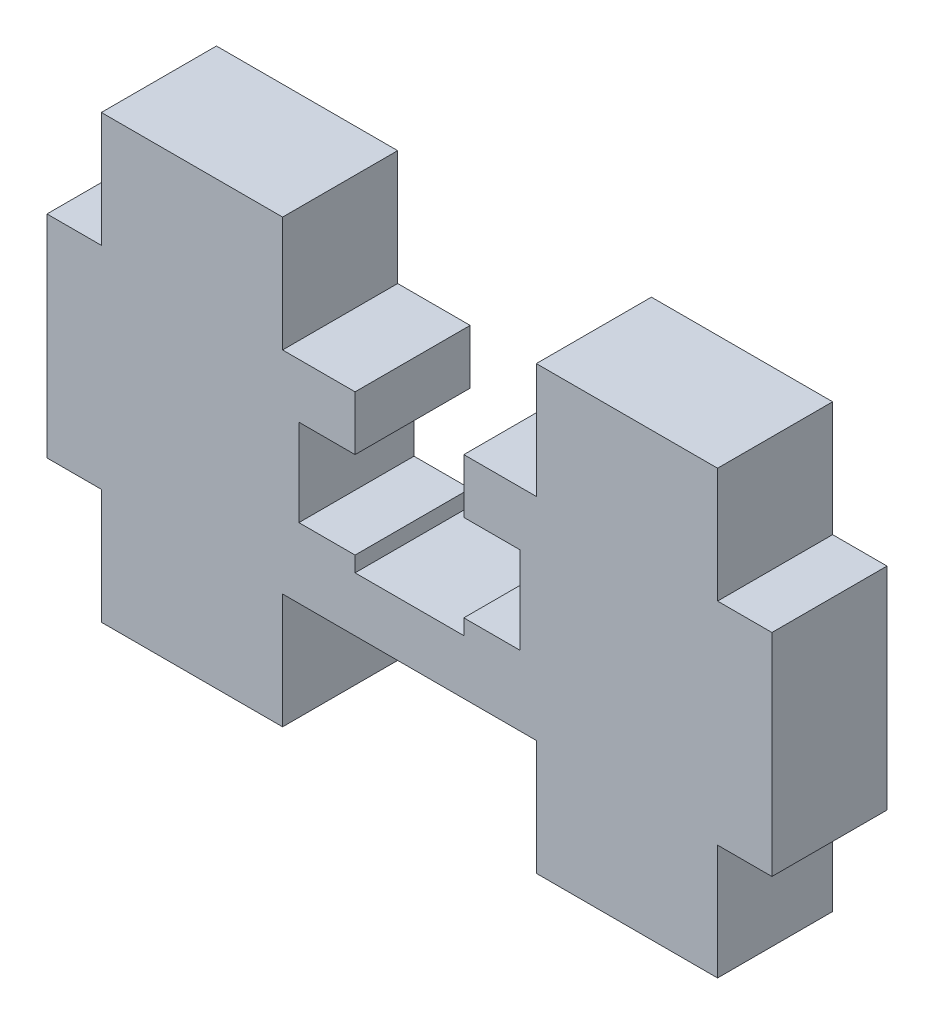
SolidWorks part; units mm, degrees
ref_plane "前视基准面" through (0, 0, 0) normal (0, 0, 1) x (1, 0, 0)
ref_plane "上视基准面" through (0, 0, 0) normal (0, 1, 0) x (1, 0, 0)
ref_plane "右视基准面" through (0, 0, 0) normal (1, 0, 0) x (0, 0, -1)
sketch "Sketch1" plane through (0, 0, 0) normal (0, 0, 1) x (1, 0, 0)
  line L0 (-5.1789, 0) -> (5.1005, 0) construction
  line L1 (0, 5.0769) -> (0, -5.0178) construction
  line L2 (-10, 2.915) -> (-10, -2.915)
  line L3 (-10, -2.915) -> (-8.5, -2.915)
  line L4 (-8.5, -2.915) -> (-8.5, -6.09)
  line L5 (-8.5, -6.09) -> (-3.5, -6.09)
  line L6 (-3.5, -6.09) -> (-3.5, -2.915)
  line L7 (-3.5, -2.915) -> (3.5, -2.915)
  line L8 (3.5, -6.09) -> (3.5, -2.915)
  line L9 (8.5, -6.09) -> (3.5, -6.09)
  line L10 (8.5, -2.915) -> (8.5, -6.09)
  line L11 (10, -2.915) -> (8.5, -2.915)
  line L12 (10, 2.915) -> (10, -2.915)
  line L13 (10, 2.915) -> (8.5, 2.915)
  line L14 (8.5, 2.915) -> (8.5, 6.09)
  line L15 (8.5, 6.09) -> (3.5, 6.09)
  line L16 (3.5, 6.09) -> (3.5, 2.915)
  line L17 (-3.5, 2.915) -> (3.5, 2.915)
  line L18 (-3.5, 6.09) -> (-3.5, 2.915)
  line L19 (-8.5, 6.09) -> (-3.5, 6.09)
  line L20 (-8.5, 2.915) -> (-8.5, 6.09)
  line L21 (-10, 2.915) -> (-8.5, 2.915)
  line L22 (-6, -6.09) -> (-6, -6.7618) construction
  line L23 (6, -6.09) -> (6, -7.2752) construction
  point P5 (0, 2.915)
  point P13 (0, -2.915)
  point P19 (10, 0)
  point P28 (-10, 0)
  point P33 (-9.25, 2.915)
  dimension "D1" = 5.83
  dimension "D2" = 5
  dimension "D3" = 20
  dimension "D4" = 12
  dimension "D5" = 3.175
extrude "Boss-Extrude1" add sketch "Sketch1" along normal blind 3.175
sketch "Sketch2" plane through (0, 0, 3.175) normal (0, 0, 1) x (1, 0, 0)
  line L0 (0, 2.915) -> (0, -4.2947) construction
  line L1 (3.5, 2.915) -> (-3.5, 2.915) construction
  line L2 (-1.5, 2.915) -> (-1.5, 1.415)
  line L3 (-1.5, 1.415) -> (-3.05, 1.415)
  line L4 (-3.05, 1.415) -> (-3.05, -0.985)
  line L5 (-3.05, -0.985) -> (-1.5, -0.985)
  line L6 (-1.5, -0.985) -> (-1.5, -1.41)
  line L7 (-1.5, -1.41) -> (1.5, -1.41)
  line L8 (-1.5, 2.915) -> (1.5, 2.915)
  line L9 (1.5, -0.985) -> (1.5, -1.41)
  line L10 (3.05, -0.985) -> (1.5, -0.985)
  line L11 (3.05, 1.415) -> (3.05, -0.985)
  line L12 (1.5, 1.415) -> (3.05, 1.415)
  line L13 (1.5, 2.915) -> (1.5, 1.415)
  line L14 (-3.5, 6.09) -> (-8.5, 6.09) construction
  point P14 (0, -1.41)
  dimension "D1" = 7.5
  dimension "D2" = 3
  dimension "D3" = 1.5
  dimension "D4" = 2.4
  dimension "D5" = 6.1
extrude "Cut-Extrude1" cut sketch "Sketch2" against normal through all
